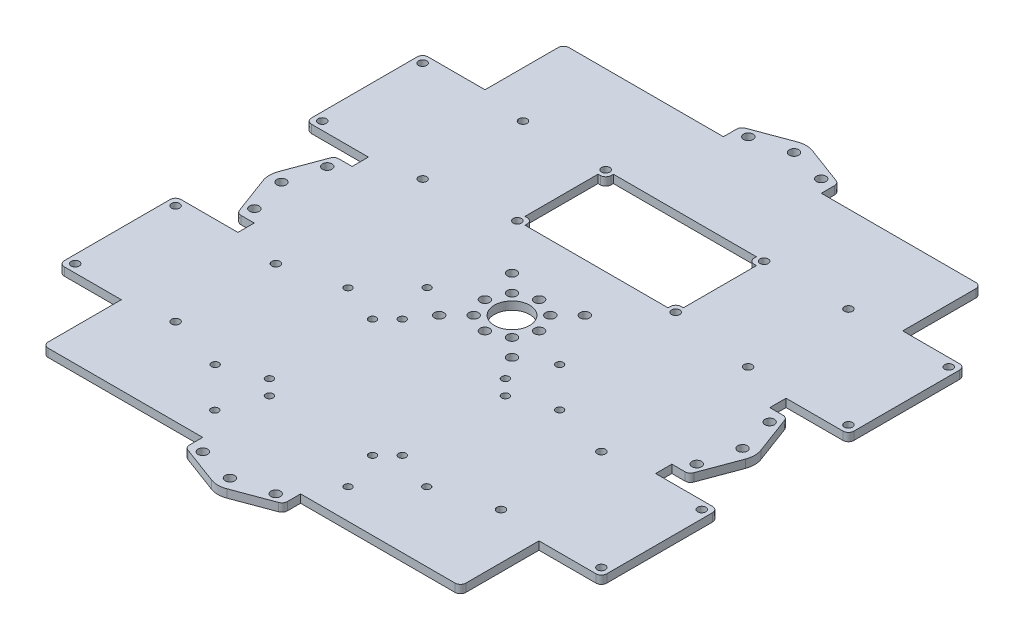
SolidWorks part; units mm, degrees
ref_plane "Plan de face" through (0, 0, 0) normal (0, 0, 1) x (1, 0, 0)
ref_plane "Plan de dessus" through (0, 0, 0) normal (0, 1, 0) x (1, 0, 0)
ref_plane "Plan de droite" through (0, 0, 0) normal (1, 0, 0) x (0, 0, -1)
sketch "Esquisse1" plane through (0, 0, 0) normal (0, 1, 0) x (1, 0, 0)
  line L0 (69.0354, 127.8675) -> (-110.9646, 127.8675)
  line L1 (-20.9646, 27.8675) -> (-20.9646, 17.8675)
  line L2 (-20.9646, 17.8675) -> (-10.9646, 17.8675)
  line L3 (-20.9646, 17.8675) -> (-13.8935, 24.9386)
  line L4 (-20.9646, 17.8675) -> (-28.0356, 24.9386)
  line L5 (-20.9646, 17.8675) -> (-30.9646, 17.8675)
  line L6 (-20.9646, 17.8675) -> (-28.0356, 10.7965)
  line L7 (-20.9646, 17.8675) -> (-13.8935, 10.7965)
  line L8 (-20.9646, 17.8675) -> (-20.9646, 7.8675)
  line L9 (-13.8935, 24.9386) -> (-7.5295, 31.3026)
  line L10 (-28.0356, 24.9386) -> (-34.3996, 31.3026)
  line L11 (-28.0356, 10.7965) -> (-34.3996, 4.4325)
  line L12 (-13.8935, 10.7965) -> (-7.5295, 4.4325)
  line L13 (-2.9146, -84.415) -> (-2.9146, -78.1325)
  line L14 (-7.5295, -86.1325) -> (-2.9146, -84.415)
  line L15 (-105.9646, 31.3026) -> (-110.9646, 17.8675)
  line L16 (-110.9646, 17.8675) -> (-105.9646, 4.4325)
  line L17 (-105.9646, 4.4325) -> (-104.2471, -0.1825)
  line L18 (-104.2471, -0.1825) -> (-97.9646, -0.1825)
  line L19 (-20.9646, -91.1325) -> (-7.5295, -86.1325)
  line L20 (-105.9646, 31.3026) -> (-104.2471, 35.9175)
  line L21 (-104.2471, 35.9175) -> (-97.9646, 35.9175)
  line L22 (69.0354, -92.1325) -> (-110.9646, -92.1325)
  line L23 (-34.3996, 121.8675) -> (-20.9646, 126.8675)
  line L24 (-97.9646, -6.1825) -> (-120.9646, -6.1825)
  line L25 (-104.2471, -6.1825) -> (-97.9646, -6.1825)
  line L26 (-34.3996, -86.1325) -> (-20.9646, -91.1325)
  line L27 (-20.9646, 126.8675) -> (-7.5295, 121.8675)
  line L28 (-39.0146, 120.15) -> (-39.0146, 113.8675)
  line L29 (-34.3996, 121.8675) -> (-39.0146, 120.15)
  line L30 (-7.5295, 121.8675) -> (-2.9146, 120.15)
  line L31 (-2.9146, 120.15) -> (-2.9146, 113.8675)
  line L32 (-120.9646, -6.1825) -> (-120.9646, -49.1825)
  line L33 (-34.3996, -86.1325) -> (-39.0146, -84.415)
  line L34 (-39.0146, -84.415) -> (-39.0146, -78.1325)
  line L35 (-39.0146, -78.1325) -> (-97.9646, -78.1325)
  line L36 (-97.9646, 113.8675) -> (-39.0146, 113.8675)
  line L37 (-2.9146, 113.8675) -> (56.0354, 113.8675)
  line L38 (62.3179, -0.1825) -> (56.0354, -0.1825)
  line L39 (64.0354, 4.4325) -> (62.3179, -0.1825)
  line L40 (69.0354, 17.8675) -> (64.0354, 4.4325)
  line L41 (64.0354, 31.3026) -> (69.0354, 17.8675)
  line L42 (64.0354, 31.3026) -> (62.3179, 35.9175)
  line L43 (62.3179, 35.9175) -> (56.0354, 35.9175)
  line L44 (-2.9146, -78.1325) -> (56.0354, -78.1325)
  line L45 (56.0354, 35.9175) -> (56.0354, 41.9175)
  line L46 (56.0354, 113.8675) -> (56.0354, 84.9175)
  line L47 (-120.9646, 41.9175) -> (-120.9646, 84.9175)
  line L48 (-97.9646, 41.9175) -> (-97.9646, 35.9175)
  line L49 (-97.9646, 41.9175) -> (-120.9646, 41.9175)
  line L50 (79.0354, -6.1825) -> (79.0354, -49.1825)
  line L51 (-97.9646, 113.8675) -> (-97.9646, 84.9175)
  line L52 (56.0354, -6.1825) -> (79.0354, -6.1825)
  line L53 (56.0354, 41.9175) -> (79.0354, 41.9175)
  line L54 (79.0354, 41.9175) -> (79.0354, 84.9175)
  line L55 (56.0354, 84.9175) -> (79.0354, 84.9175)
  line L56 (56.0354, -0.1825) -> (56.0354, -6.1825)
  line L57 (56.0354, -78.1325) -> (56.0354, -49.1825)
  line L58 (79.0354, -49.1825) -> (56.0354, -49.1825)
  line L59 (-97.9646, -78.1325) -> (-97.9646, -49.1825)
  line L60 (-120.9646, -49.1825) -> (-97.9646, -49.1825)
  line L61 (-97.9646, -0.1825) -> (-97.9646, -6.1825)
  line L62 (-120.9646, 84.9175) -> (-97.9646, 84.9175)
  line L63 (-50.1646, 78.7891) -> (-47.3361, 78.7891)
  line L69 (-47.3361, 81.6175) -> (5.407, 81.6175)
  line L70 (7.0354, 14.4175) -> (3.5354, 14.4175)
  line L71 (5.407, 78.7891) -> (8.2354, 78.7891)
  line L72 (-47.3361, 78.7891) -> (-50.1646, 78.7891)
  line L73 (-50.1646, 78.7891) -> (-47.3361, 78.7891)
  line L74 (-47.3361, 78.7891) -> (-47.3361, 81.6175)
  line L78 (8.2354, 51.8544) -> (5.407, 51.8544)
  line L79 (5.407, 78.7891) -> (5.407, 81.6175)
  line L80 (5.407, 81.6175) -> (-47.3361, 81.6175)
  line L81 (5.407, 78.7891) -> (8.2354, 78.7891)
  line L82 (8.2354, 78.7891) -> (8.2354, 51.8544)
  line L83 (8.2354, 51.8544) -> (5.407, 51.8544)
  line L84 (5.407, 51.8544) -> (5.407, 49.026)
  line L85 (5.407, 49.026) -> (-47.3361, 49.026)
  line L86 (-47.3361, 49.026) -> (-47.3361, 51.8544)
  line L87 (-47.3361, 51.8544) -> (-50.1646, 51.8544)
  line L88 (-50.1646, 51.8544) -> (-50.1646, 78.7891)
  line L89 (5.407, 51.8544) -> (5.407, 49.026)
  line L90 (-50.1646, 78.7891) -> (-47.3361, 78.7891)
  line L91 (-47.3361, 78.7891) -> (-47.3361, 81.6175)
  circle A0 centre (-20.9646, 17.8675) radius 6.5
  circle A1 centre (-20.9646, 27.8675) radius 1.75
  circle A2 centre (-13.8935, 24.9386) radius 1.75
  circle A3 centre (-10.9646, 17.8675) radius 1.75
  circle A4 centre (-13.8935, 10.7965) radius 1.75
  circle A5 centre (-20.9646, 7.8675) radius 1.75
  circle A6 centre (-28.0356, 10.7965) radius 1.75
  circle A7 centre (-30.9646, 17.8675) radius 1.75
  circle A8 centre (-28.0356, 24.9386) radius 1.75
  circle A9 centre (-7.5295, 31.3026) radius 1.75
  circle A10 centre (-7.5295, 4.4325) radius 1.75
  circle A11 centre (-34.3996, 31.3026) radius 1.75
  circle A12 centre (-34.3996, 4.4325) radius 1.75
  circle A13 centre (64.0354, 17.8675) radius 1.75
  circle A14 centre (60.6004, 31.3026) radius 1.75
  circle A15 centre (60.6004, 4.4325) radius 1.75
  circle A16 centre (-102.5295, 4.4325) radius 1.75
  circle A17 centre (-105.9646, 17.8675) radius 1.75
  circle A18 centre (-102.5295, 31.3026) radius 1.75
  circle A19 centre (-20.9646, -86.1325) radius 1.75
  circle A20 centre (-7.5295, -82.6974) radius 1.75
  circle A21 centre (-34.3996, -82.6974) radius 1.75
  circle A22 centre (-34.3996, 118.4325) radius 1.75
  circle A23 centre (-20.9646, 121.8675) radius 1.75
  circle A24 centre (-7.5295, 118.4325) radius 1.75
  circle A25 centre (-117.9646, -46.1825) radius 1.5
  circle A26 centre (-117.9646, -9.1825) radius 1.5
  circle A27 centre (-80.9646, -9.1825) radius 1.5
  circle A28 centre (-80.9646, -46.1825) radius 1.5
  circle A29 centre (-80.9646, 81.9175) radius 1.5
  circle A30 centre (-80.9646, 44.9175) radius 1.5
  circle A31 centre (-117.9646, 44.9175) radius 1.5
  circle A32 centre (-117.9646, 81.9175) radius 1.5
  circle A33 centre (39.0354, -46.1825) radius 1.5
  circle A34 centre (39.0354, -9.1825) radius 1.5
  circle A35 centre (76.0354, -9.1825) radius 1.5
  circle A36 centre (76.0354, -46.1825) radius 1.5
  circle A37 centre (76.0354, 81.9175) radius 1.5
  circle A38 centre (76.0354, 44.9175) radius 1.5
  circle A39 centre (39.0354, 44.9175) radius 1.5
  circle A40 centre (39.0354, 81.9175) radius 1.5
  circle A41 centre (-50.1646, 81.6175) radius 1.5
  circle A42 centre (8.2354, 81.6175) radius 1.5
  circle A43 centre (-50.1646, 49.026) radius 1.5
  circle A44 centre (8.2354, 49.026) radius 1.5
  circle A45 centre (3.5354, 10.9175) radius 1.35
  circle A46 centre (-45.4646, 11.0636) radius 1.35
  circle A47 centre (-45.4646, -47.0825) radius 1.35
  circle A48 centre (3.5354, -47.0825) radius 1.35
  circle A50 centre (-59.9646, -3.5825) radius 1.35
  circle A51 centre (-59.9646, -52.5825) radius 1.35
  circle A52 centre (-1.9646, -3.5825) radius 1.35
  circle A53 centre (-1.9646, -52.5825) radius 1.35
  circle A54 centre (-39.9646, -3.5825) radius 1.35
  circle A55 centre (-39.9646, -52.5825) radius 1.35
  circle A56 centre (18.0354, -52.5825) radius 1.35
  circle A57 centre (18.0354, -3.5825) radius 1.35
  circle A58 centre (-45.4646, -67.2286) radius 1.35
  circle A59 centre (3.5354, -67.0825) radius 1.35
  circle A60 centre (3.5354, -9.0825) radius 1.35
  circle A61 centre (-45.4646, -9.0825) radius 1.35
  dimension "D1" = 180
  dimension "D2" = 220
extrude "Boss.-Extru.1" add sketch "Esquisse1" along normal blind 3
fillet "Congé2" radius 2 12 edges at (56.0354, 1.5, -113.8675) (79.0354, 1.5, -84.9175) (79.0354, 1.5, -41.9175) (79.0354, 1.5, 6.1825) (79.0354, 1.5, 49.1825) (56.0354, 1.5, 78.1325) (-97.9646, 1.5, -113.8675) (-120.9646, 1.5, -84.9175) (-120.9646, 1.5, -41.9175) (-120.9646, 1.5, 6.1825) (-120.9646, 1.5, 49.1825) (-97.9646, 1.5, 78.1325)
fillet "Congé3" radius 2 4 edges at (5.407, 1.5, -51.8544) (5.407, 1.5, -78.7891) (-47.3361, 1.5, -78.7891) (-47.3361, 1.5, -51.8544)
fillet "Congé4" radius 2 8 edges at (62.3179, 1.5, -35.9175) (62.3179, 1.5, 0.1825) (-2.9146, 1.5, 84.415) (-39.0146, 1.5, 84.415) (-104.2471, 1.5, 0.1825) (-104.2471, 1.5, -35.9175) (-39.0146, 1.5, -120.15) (-2.9146, 1.5, -120.15)
fillet "Congé5" radius 8 4 edges at (69.0354, 1.5, -17.8675) (-20.9646, 1.5, 91.1325) (-110.9646, 1.5, -17.8675) (-20.9646, 1.5, -126.8675)
